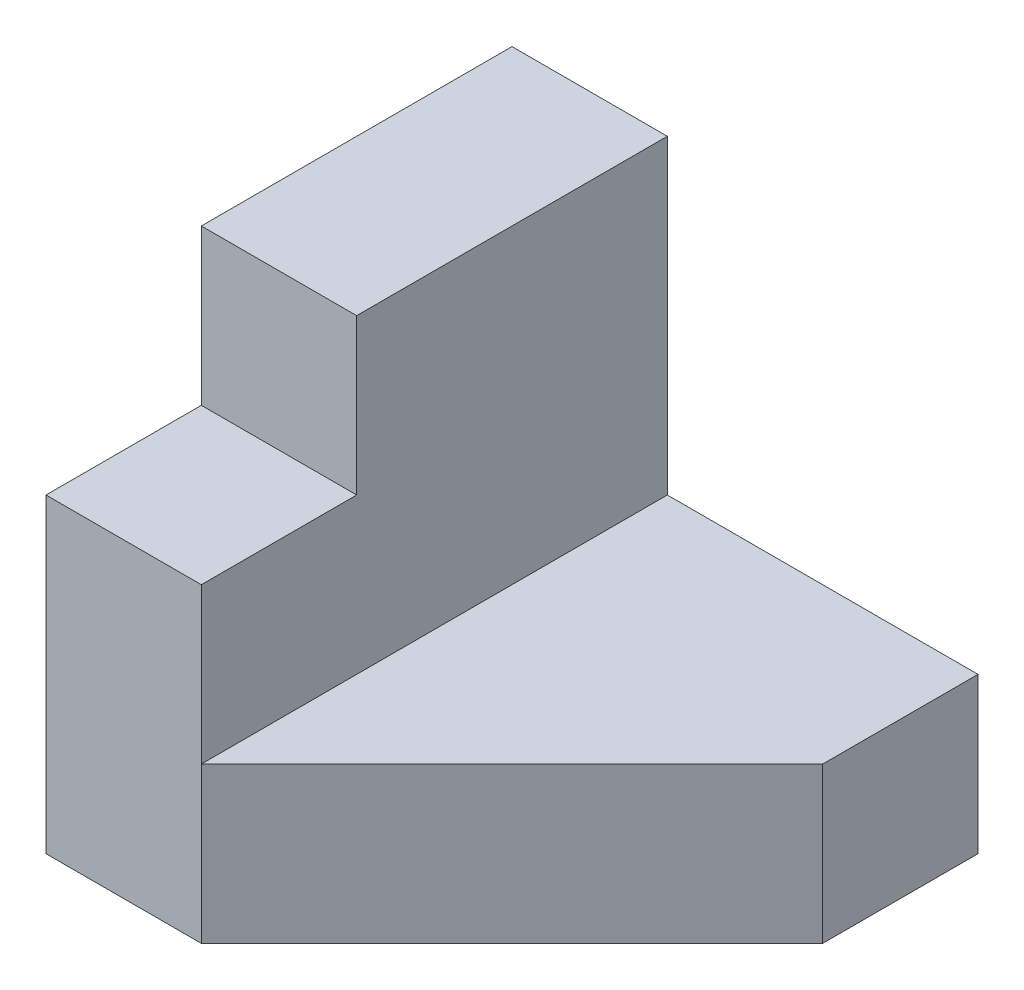
SolidWorks part; units mm, degrees
ref_plane "前基準面" through (0, 0, 0) normal (0, 0, 1) x (1, 0, 0)
ref_plane "上基準面" through (0, 0, 0) normal (0, 1, 0) x (1, 0, 0)
ref_plane "右基準面" through (0, 0, 0) normal (1, 0, 0) x (0, 0, -1)
sketch "草圖1" plane through (0, 0, 0) normal (0, 0, 1) x (1, 0, 0)
  line L1 (0, 0) -> (30, 0)
  line L2 (0, 0) -> (0, 30)
  line L3 (0, 30) -> (30, 30)
  line L4 (30, 0) -> (30, 30)
  dimension "D1" = 30
  dimension "D2" = 30
extrude "填料-伸1" add sketch "草圖1" against normal blind 30
sketch "草圖34" plane through (0, 0, 0) normal (0, 0, 1) x (1, 0, 0)
  line L1 (30, 30) -> (10, 30)
  line L2 (30, 30) -> (30, 10)
  line L3 (30, 10) -> (10, 10)
  line L4 (10, 30) -> (10, 10)
  dimension "D1" = 20
  dimension "D2" = 20
extrude "除料-伸長23" cut sketch "草圖34" against normal through all
sketch "草圖35" plane through (10, 0, 0) normal (1, 0, 0) x (0, 0, -1)
  line L1 (0, 30) -> (10, 30)
  line L2 (0, 30) -> (0, 20)
  line L3 (0, 20) -> (10, 20)
  line L4 (10, 30) -> (10, 20)
  dimension "D1" = 10
  dimension "D2" = 10
extrude "除料-伸長24" cut sketch "草圖35" against normal through all
sketch "草圖36" plane through (0, 10, 0) normal (0, 1, 0) x (1, 0, 0)
  line L0 (10, 0) -> (30, 20)
  line L1 (-16.5, 0) -> (16.5, 0) construction
  line L2 (10, 0) -> (10, 10) construction
  line L3 (30, 30) -> (30, 0) construction
  line L4 (30, 20) -> (30, 0)
  line L5 (10, 0) -> (30, 0)
  dimension "D1" = 20
  dimension "D2" = 20
extrude "除料-伸長25" cut sketch "草圖36" against normal through all
